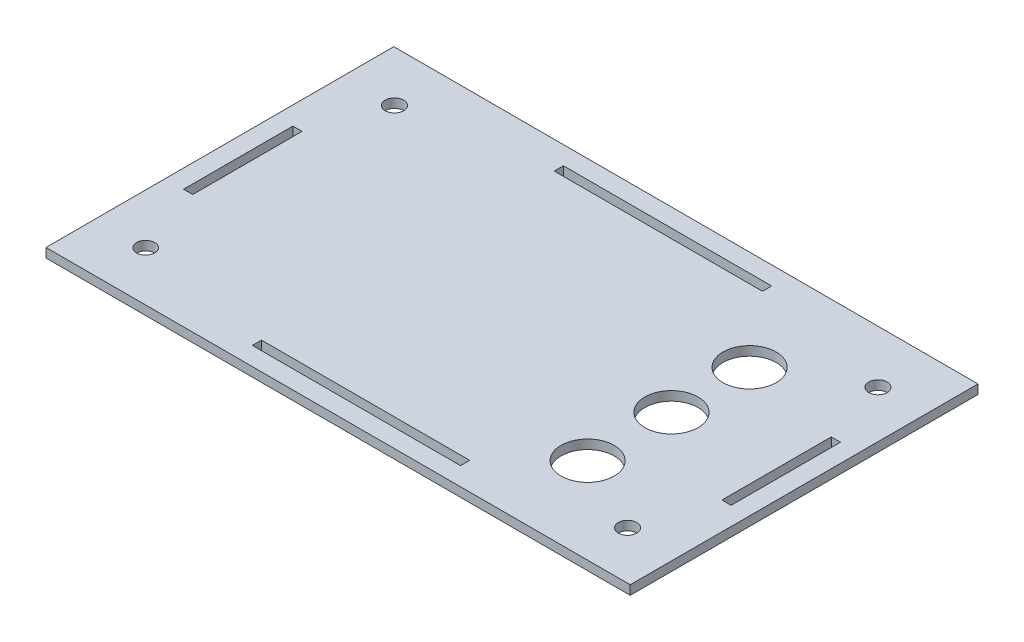
SolidWorks part; units mm, degrees
ref_plane "Front Plane" through (0, 0, 0) normal (0, 0, 1) x (1, 0, 0)
ref_plane "Top Plane" through (0, 0, 0) normal (0, 1, 0) x (1, 0, 0)
ref_plane "Right Plane" through (0, 0, 0) normal (1, 0, 0) x (0, 0, -1)
sketch "Sketch2" plane through (0, 0, 0) normal (0, 1, 0) x (1, 0, 0)
  line L9 (-7.2235, 68.6261) -> (120.1865, 68.6261)
  line L10 (-7.2235, 68.6261) -> (-7.2235, -7.2219)
  line L11 (-7.2235, -7.2219) -> (120.1865, -7.2219)
  line L12 (120.1865, 68.6261) -> (120.1865, -7.2219)
  line L15 (-5.2235, 66.6261) -> (118.1865, 66.6261) construction
  line L16 (-5.2235, 66.6261) -> (-5.2235, -5.2219) construction
  line L17 (-5.2235, -5.2219) -> (118.1865, -5.2219) construction
  line L18 (118.1865, 66.6261) -> (118.1865, -5.2219) construction
  line L19 (-1.2235, 42.6261) -> (-3.2235, 42.6261)
  line L20 (-1.2235, 42.6261) -> (-1.2235, 18.7781)
  line L21 (-1.2235, 18.7781) -> (-3.2235, 18.7781)
  line L22 (-3.2235, 42.6261) -> (-3.2235, 18.7781)
  line L23 (33.7765, 62.6261) -> (79.1865, 62.6261)
  line L24 (33.7765, 62.6261) -> (33.7765, 64.6261)
  line L25 (33.7765, 64.6261) -> (79.1865, 64.6261)
  line L26 (79.1865, 62.6261) -> (79.1865, 64.6261)
  line L27 (114.1865, 42.6261) -> (116.1865, 42.6261)
  line L28 (114.1865, 42.6261) -> (114.1865, 18.7781)
  line L29 (114.1865, 18.7781) -> (116.1865, 18.7781)
  line L30 (116.1865, 42.6261) -> (116.1865, 18.7781)
  line L31 (79.1865, -1.2219) -> (33.7765, -1.2219)
  line L32 (79.1865, -1.2219) -> (79.1865, -3.2219)
  line L33 (79.1865, -3.2219) -> (33.7765, -3.2219)
  line L34 (33.7765, -1.2219) -> (33.7765, -3.2219)
  circle A0 centre (3.7765, 3.7781) radius 1.3609 construction
  circle A1 centre (109.1865, 3.7781) radius 1.3609 construction
  circle A2 centre (3.7765, 57.6261) radius 1.6 construction
  circle A3 centre (109.1865, 57.6261) radius 1.3609 construction
  circle A4 centre (92.1137, 29.8506) radius 5.8
  circle A5 centre (92.1137, 11.5633) radius 5.8
  circle A6 centre (92.1319, 46.8635) radius 5.8
  circle A7 centre (3.6953, 3.5852) radius 1.9754
  circle A10 centre (3.9452, 57.6066) radius 2.0206
  circle A11 centre (109.9031, 57.0856) radius 2.0058
  circle A12 centre (109.1405, 3.2382) radius 2.0076
  point P34 (33.7765, -2.2219)
  point P35 (115.1865, 42.6261)
  point P50 (0, 0)
  point P51 (0, 0)
  point P52 (-5.2235, 65.5117)
  dimension "D20" = 2
  dimension "D2" = 2
  dimension "D3" = 15
  dimension "D4" = 15
  dimension "D5" = 30
  dimension "D6" = 30
  dimension "D7" = 30
  dimension "D8" = 30
  dimension "D9" = 15
  dimension "D10" = 15
  dimension "D11" = 5
  dimension "D12" = 2
  dimension "D13" = 5
  dimension "D14" = 5
  dimension "D15" = 5
  dimension "D16" = 9
  dimension "D17" = 9
  dimension "D18" = 9
  dimension "D19" = 9
  dimension "D21" = 2
  dimension "D22" = 2
extrude "Boss-Extrude1" add sketch "Sketch2" along normal blind 2
